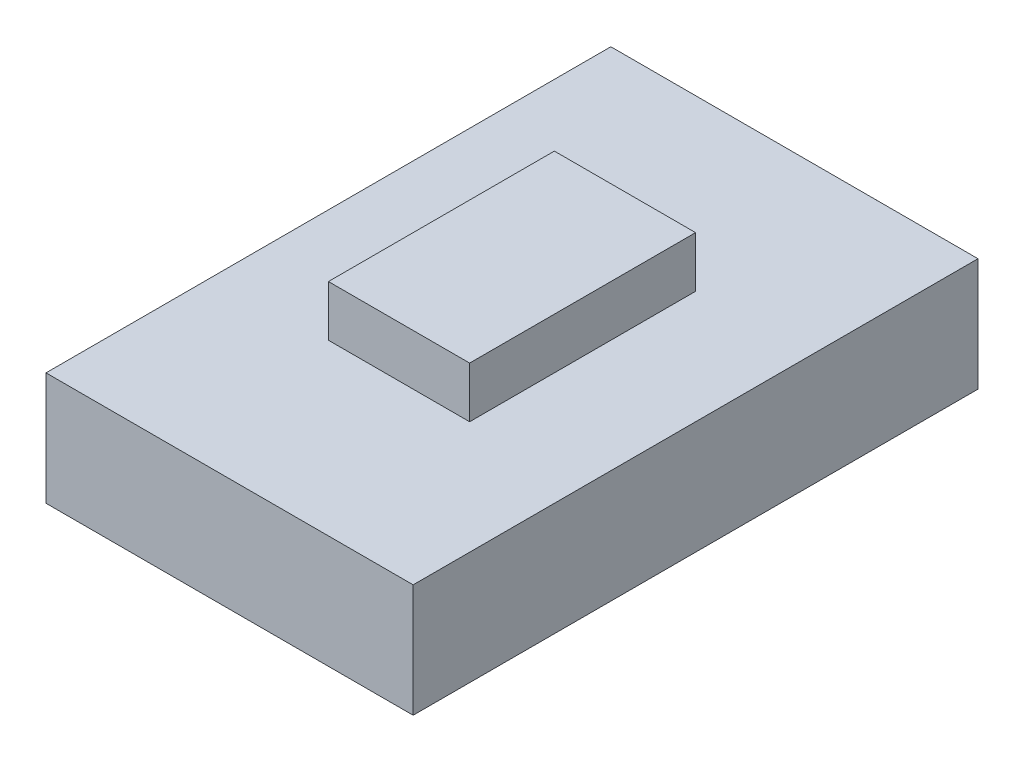
SolidWorks part; units mm, degrees
ref_plane "Front Plane" through (0, 0, 0) normal (0, 0, 1) x (1, 0, 0)
ref_plane "Top Plane" through (0, 0, 0) normal (0, 1, 0) x (1, 0, 0)
ref_plane "Right Plane" through (0, 0, 0) normal (1, 0, 0) x (0, 0, -1)
sketch "Sketch1" plane through (0, 0, 0) normal (0, 1, 0) x (1, 0, 0)
  line L0 (0, 0) -> (0, 2)
  line L1 (0, 2) -> (1.25, 2)
  line L2 (1.25, 2) -> (1.25, 0)
  line L3 (1.25, 0) -> (0, 0)
extrude "Boss-Extrude1" add sketch "Sketch1" along normal blind 0.45
sketch "Sketch2" plane through (0, 0, 0) normal (0, -1, 0) x (1, 0, 0)
  line L0 (0.5606, -3.5) -> (0.625, -3.5)
  line L17 (0.625, -3.5) -> (2.25, -3.5)
  line L18 (2.25, -3.5) -> (2.25, 1.5)
  line L19 (2.25, 1.5) -> (-1, 1.5)
  line L20 (-1, 1.5) -> (-1, -3.5)
  line L21 (-1, -3.5) -> (0.5606, -3.5)
extrude "Boss-Extrude3" add sketch "Sketch2" along normal blind 1
